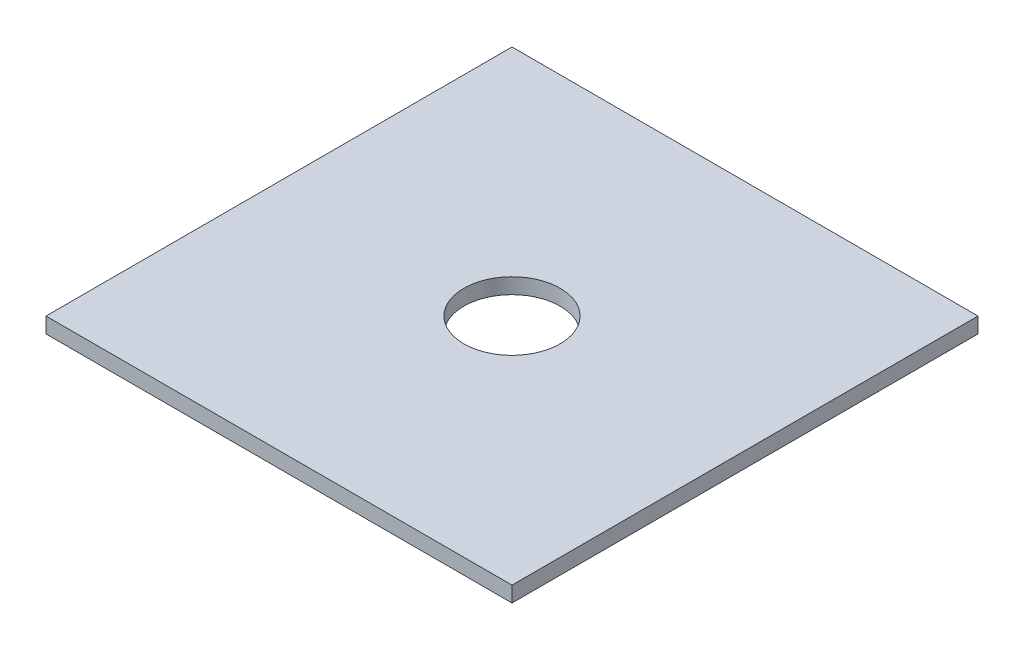
SolidWorks part; units mm, degrees
ref_plane "Front Plane" through (0, 0, 0) normal (0, 0, 1) x (1, 0, 0)
ref_plane "Top Plane" through (0, 0, 0) normal (0, 1, 0) x (1, 0, 0)
ref_plane "Right Plane" through (0, 0, 0) normal (1, 0, 0) x (0, 0, -1)
sketch "Sketch2" plane through (0, 0, 0) normal (0, 1, 0) x (1, 0, 0)
  line L1 (-15, 15) -> (15, 15)
  line L2 (-15, 15) -> (-15, -15)
  line L3 (-15, -15) -> (15, -15)
  line L4 (15, 15) -> (15, -15)
  line L5 (-15, 15) -> (15, -15) construction
  line L6 (-15, -15) -> (15, 15) construction
  point P0 (0, 0)
  dimension "D1" = 30
  dimension "D2" = 30
extrude "Boss-Extrude1" add sketch "Sketch2" along normal blind 10 contours L2 L1 L4 L3
sketch "Sketch3" plane through (0, 10, 0) normal (0, 1, 0) x (1, 0, 0)
  line L1 (-15, 15) -> (15, 15)
  line L2 (-15, 15) -> (-15, -15)
  line L3 (-15, -15) -> (15, -15)
  line L4 (15, 15) -> (15, -15)
  line L5 (-15, 15) -> (15, -15) construction
  line L6 (-15, -15) -> (15, 15) construction
  line L7 (-12.5, 12.5) -> (12.5, 12.5)
  line L8 (-12.5, 12.5) -> (-12.5, -12.5)
  line L9 (-12.5, -12.5) -> (12.5, -12.5)
  line L10 (12.5, 12.5) -> (12.5, -12.5)
  line L11 (-12.5, 12.5) -> (12.5, -12.5) construction
  line L12 (-12.5, -12.5) -> (12.5, 12.5) construction
  point P0 (0, 0)
  point P7 (0, 0)
  dimension "D1" = 25
extrude "Boss-Extrude2" add sketch "Sketch3" along normal blind 15 separate body
sketch "Sketch4" plane through (0, 25, 0) normal (0, 1, 0) x (1, 0, 0)
  line L1 (-15, 15) -> (15, 15)
  line L2 (-15, 15) -> (-15, -15)
  line L3 (-15, -15) -> (15, -15)
  line L4 (15, 15) -> (15, -15)
  line L5 (-15, 15) -> (15, -15) construction
  line L6 (-15, -15) -> (15, 15) construction
  point P0 (0, 0)
extrude "Boss-Extrude3" add sketch "Sketch4" along normal blind 15 separate body
sketch "Sketch5" plane through (0, 40, 0) normal (0, 1, 0) x (1, 0, 0)
  circle A0 centre (0, 0) radius 3.05
extrude "Cut-Extrude1" cut sketch "Sketch5" against normal up to surface (40 mm away)
delete or keep bodies "Body-Delete/Keep 2" type delete bodies bodies 102 104
sketch "Sketch6" plane through (0, 0, -15) normal (0, 0, -1) x (-1, 0, 0)
  line L1 (-15, 25) -> (-7.5, 25)
  line L2 (-15, 25) -> (-15, 26.0178)
  line L3 (-15, 26.0178) -> (-7.5, 26.0178)
  line L4 (-7.5, 25) -> (-7.5, 26.0178)
  line L5 (15, 25) -> (7.5, 25)
  line L6 (15, 25) -> (15, 26.2762)
  line L7 (15, 26.2762) -> (7.5, 26.2762)
  line L8 (7.5, 25) -> (7.5, 26.2762)
  dimension "D1" = 7.5
  dimension "D2" = 7.5
extrude "Boss-Extrude4" add sketch "Sketch6" along normal blind 10 and the other way blind 40
sketch "Sketch7" plane through (0, 26.2762, 0) normal (0, 1, 0) x (1, 0, 0)
  line L0 (-15, 20) -> (-7.5, 20) construction
  line L1 (-15, 15) -> (-15, 25) construction
  line L2 (-7.5, 15) -> (-7.5, 25) construction
  line L3 (15.1236, 20) -> (7.5761, 20) construction
  circle A0 centre (-11.25, 20) radius 2.76
  circle A1 centre (11.25, 20) radius 2.76
  circle A2 centre (11.25, -20.5) radius 2.76
  circle A3 centre (-11.25, -20.5) radius 2.76
  dimension "D1" = 5.52
  dimension "D2" = 2
  dimension "D3" = 2
extrude "Cut-Extrude2" cut sketch "Sketch7" against normal blind 10 contours A0 | A1 | A3 | A2
sketch "Sketch8" plane through (0, 40, 0) normal (0, 1, 0) x (1, 0, 0)
  line L0 (15, -15) -> (15, 15) construction
  line L1 (-15, 15) -> (15, 15)
  line L2 (-15, 15) -> (-15, -15)
  line L3 (-15, -15) -> (15, -15)
  line L4 (15, 15) -> (15, -15)
  line L5 (-15, 15) -> (15, -15) construction
  line L6 (-15, -15) -> (15, 15) construction
  line L7 (-15, -15) -> (15, -15) construction
  point P0 (0, 0)
extrude "Boss-Extrude5" add sketch "Sketch8" along normal blind 1 separate body
sketch "Sketch9" plane through (0, 41, 0) normal (0, 1, 0) x (1, 0, 0)
  circle A0 centre (0, 0) radius 3.1
  dimension "D1" = 6.2
extrude "Cut-Extrude3" cut sketch "Sketch9" against normal blind 1
delete or keep bodies "Body-Delete/Keep 3" type delete bodies bodies 107
